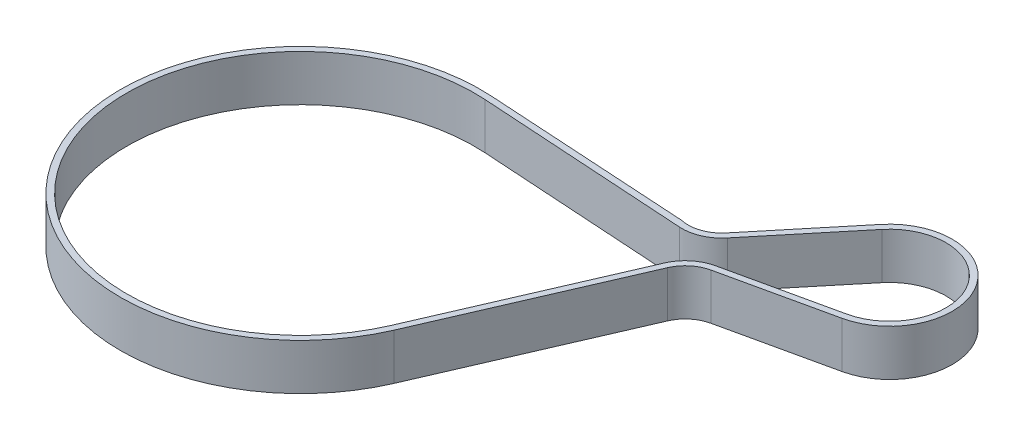
SolidWorks part; units mm, degrees
ref_plane "Front Plane" through (0, 0, 0) normal (0, 0, 1) x (1, 0, 0)
ref_plane "Top Plane" through (0, 0, 0) normal (0, 1, 0) x (1, 0, 0)
ref_plane "Right Plane" through (0, 0, 0) normal (1, 0, 0) x (0, 0, -1)
sketch "Sketch1" plane through (0, 0, 0) normal (0, 1, 0) x (1, 0, 0)
  line L0 (18.6219, 16.2605) -> (29.9995, 30.0446)
  line L1 (21.6016, 11.3923) -> (39.0527, 15.2538)
  line L2 (13.196, 13.9113) -> (-20.5376, 16.059)
  line L3 (17.0413, 7.629) -> (3.6079, -23.3889)
  line L4 (-20.5376, 17.0609) -> (12.3809, 15.0371)
  line L5 (4.5255, -23.7863) -> (17.959, 7.2316)
  line L6 (29.2282, 30.6812) -> (17.8507, 16.8971)
  line L7 (39.2688, 14.2774) -> (21.8177, 10.4159)
  circle A0 centre (37.0715, 24.2072) radius 9.17
  circle A1 centre (13.609, 20.3982) radius 5.5
  circle A2 centre (23.006, 5.0458) radius 5.5
  circle A3 centre (13.609, 20.3982) radius 6.5
  circle A4 centre (23.006, 5.0458) radius 6.5
  circle A5 centre (37.0715, 24.2072) radius 10.17
  circle A6 centre (-22.3338, -12.1539) radius 28.27
  circle A7 centre (-22.3338, -12.1539) radius 29.27
extrude "Boss-Extrude1" add sketch "Sketch1" along normal blind 7 contours A7 L3 A6 L2 | A7 L5 A4 L3 | A7 L2 A3 L4 | A3 L6 A1 L4 | L7 A4 L5 A2 | A5 L1 A4 L7 | A5 L6 A3 L0 | A5 L0 A0 L1
sketch "Sketch2" plane through (0, 7, 0) normal (0, 1, 0) x (1, 0, 0)
  line L0 (4.5255, -23.7863) -> (17.959, 7.2316) construction
  line L1 (39.2688, 14.2774) -> (21.8177, 10.4159) construction
  line L2 (29.2282, 30.6812) -> (17.8507, 16.8971) construction
  line L3 (-20.5376, 17.0609) -> (12.3809, 15.0371) construction
  line L4 (21.6016, 11.3923) -> (39.0527, 15.2538)
  line L5 (3.6079, -23.3889) -> (17.0413, 7.629)
  line L6 (13.196, 13.9113) -> (-20.5376, 16.059)
  line L7 (29.9995, 30.0446) -> (18.6219, 16.2605)
  line L8 (21.6016, 11.3923) -> (39.0527, 15.2538)
  line L9 (3.6079, -23.3889) -> (17.0413, 7.629)
  line L10 (13.196, 13.9113) -> (-20.5376, 16.059)
  line L11 (29.9995, 30.0446) -> (18.6219, 16.2605)
  line L12 (4.5255, -23.7863) -> (17.959, 7.2316)
  line L13 (39.2688, 14.2774) -> (21.8177, 10.4159)
  line L14 (29.2282, 30.6812) -> (17.8507, 16.8971)
  line L15 (-20.5376, 17.0609) -> (12.3809, 15.0371)
  arc A0 (21.8177, 10.4159) -> (17.959, 7.2316) centre (23.006, 5.0458) ccw construction
  arc A1 (39.2688, 14.2774) -> (29.2282, 30.6812) centre (37.0715, 24.2072) ccw construction
  arc A2 (12.3809, 15.0371) -> (17.8507, 16.8971) centre (13.609, 20.3982) ccw construction
  arc A3 (-20.5376, 17.0609) -> (4.5255, -23.7863) centre (-22.3338, -12.1539) ccw construction
  arc A4 (39.0527, 15.2538) -> (29.9995, 30.0446) centre (37.0715, 24.2072) ccw
  arc A5 (21.6016, 11.3923) -> (17.0413, 7.629) centre (23.006, 5.0458) ccw
  arc A6 (-20.5376, 16.059) -> (3.6079, -23.3889) centre (-22.3338, -12.1539) ccw
  arc A7 (13.196, 13.9113) -> (18.6219, 16.2605) centre (13.609, 20.3982) ccw
  arc A8 (39.0527, 15.2538) -> (29.9995, 30.0446) centre (37.0715, 24.2072) ccw
  arc A9 (21.6016, 11.3923) -> (17.0413, 7.629) centre (23.006, 5.0458) ccw
  arc A10 (-20.5376, 16.059) -> (3.6079, -23.3889) centre (-22.3338, -12.1539) ccw
  arc A11 (13.196, 13.9113) -> (18.6219, 16.2605) centre (13.609, 20.3982) ccw
  arc A12 (21.8177, 10.4159) -> (17.959, 7.2316) centre (23.006, 5.0458) ccw
  arc A13 (39.2688, 14.2774) -> (29.2282, 30.6812) centre (37.0715, 24.2072) ccw
  arc A14 (12.3809, 15.0371) -> (17.8507, 16.8971) centre (13.609, 20.3982) ccw
  arc A15 (-20.5376, 17.0609) -> (4.5255, -23.7863) centre (-22.3338, -12.1539) ccw
  dimension "D1" = 0
extrude "Boss-Extrude2" add sketch "Sketch2" along normal blind 0.5
